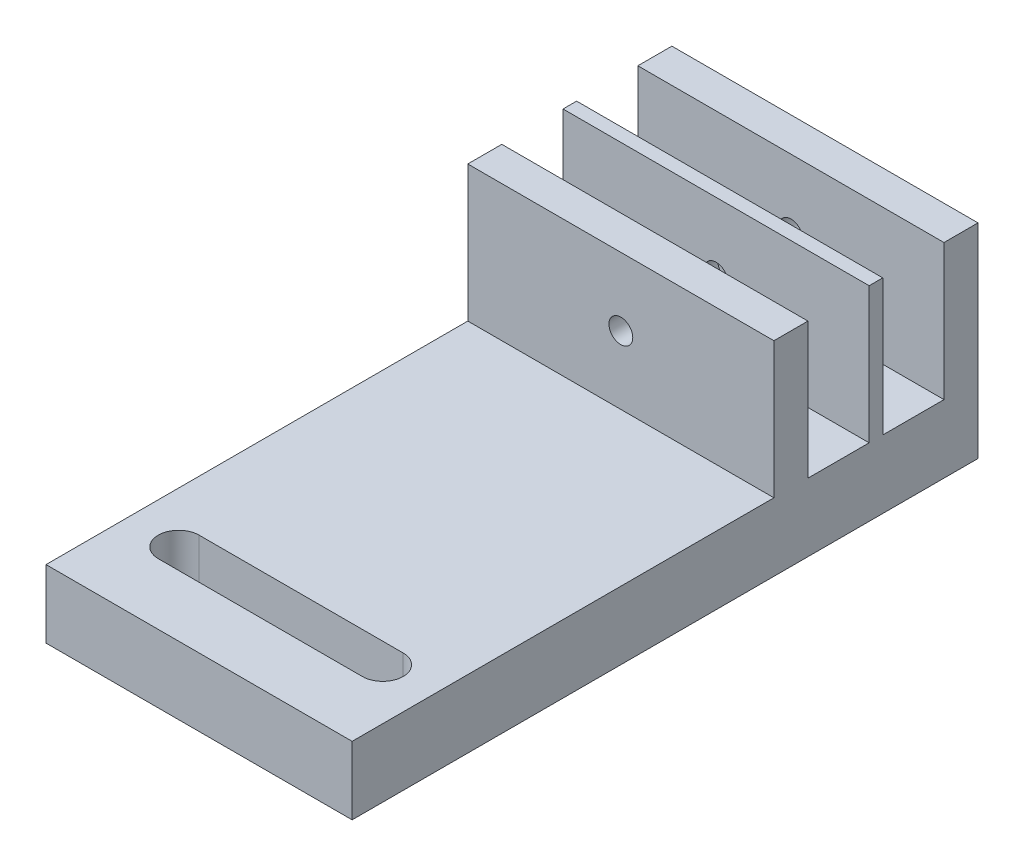
SolidWorks part; units mm, degrees
ref_plane "Front Plane" through (0, 0, 0) normal (0, 0, 1) x (1, 0, 0)
ref_plane "Top Plane" through (0, 0, 0) normal (0, 1, 0) x (1, 0, 0)
ref_plane "Right Plane" through (0, 0, 0) normal (1, 0, 0) x (0, 0, -1)
sketch "Sketch1" plane through (0, 0, 0) normal (0, 1, 0) x (1, 0, 0)
  line L0 (0, -55) -> (0, 55) construction
  line L1 (22.5, -28.5) -> (-22.5, -28.5)
  line L2 (22.5, -28.5) -> (22.5, 28.5)
  line L3 (22.5, 28.5) -> (-22.5, 28.5)
  line L4 (-22.5, -28.5) -> (-22.5, 28.5)
  line L5 (22.5, -28.5) -> (-22.5, 28.5) construction
  line L6 (22.5, 28.5) -> (-22.5, -28.5) construction
  line L7 (22.5, 18.5) -> (-22.5, 18.5) construction
  line L9 (-15, -13.5) -> (15, -13.5)
  line L10 (-15, -13.5) -> (-15, -19.5)
  line L11 (-15, -19.5) -> (15, -19.5)
  line L12 (15, -13.5) -> (15, -19.5)
  circle A0 centre (-15, -16.5) radius 3
  circle A1 centre (15, -16.5) radius 3
  point P0 (0, 0)
  dimension "D2" = 6
  dimension "D1" = 30
  dimension "D3" = 47
  dimension "D4" = 57
  dimension "D5" = 35
  dimension "D6" = 45
  dimension "D7" = 45
extrude "Boss-Extrude1" add sketch "Sketch1" along normal blind 10 contours L4 L1 L2 L3 L9 A1 L11 A0
sketch "Sketch4" plane through (0, 0, -28.5) normal (0, 0, -1) x (-1, 0, 0)
  line L0 (22.5, 0) -> (-31.8826, 0) construction
  line L2 (-22.5, 10) -> (22.5, 10)
  line L3 (-22.5, 10) -> (-22.5, 0)
  line L4 (-22.5, 0) -> (22.5, 0)
  line L5 (22.5, 10) -> (22.5, 0)
extrude "Boss-Extrude4" add sketch "Sketch4" along normal blind 35
sketch "Sketch5" plane through (22.5, 0, 0) normal (1, 0, 0) x (0, 0, -1)
  line L0 (-28.5, 10) -> (63.5, 10) construction
  line L5 (38.5, 10) -> (33.5, 10)
  line L6 (38.5, 10) -> (38.5, 30)
  line L7 (38.5, 30) -> (33.5, 30)
  line L8 (33.5, 10) -> (33.5, 30)
  line L9 (-13.5, 10) -> (-19.5, 10) construction
  line L10 (63.5, 10) -> (58.5, 10)
  line L11 (63.5, 10) -> (63.5, 30)
  line L12 (63.5, 30) -> (58.5, 30)
  line L13 (58.5, 10) -> (58.5, 30)
  line L14 (49.5, 10) -> (47.5, 10)
  line L15 (49.5, 10) -> (49.5, 30)
  line L16 (49.5, 30) -> (47.5, 30)
  line L17 (47.5, 10) -> (47.5, 30)
  line L18 (-13.5, 10) -> (-19.5, 10)
  line L19 (-16.5, 10) -> (-16.5, 0) construction
  line L23 (-19.5, 0) -> (-13.5, 0)
  line L24 (-13.5, 0) -> (-13.5, 10)
  line L25 (-13.5, 10) -> (-19.5, 10)
  line L26 (-19.5, 10) -> (-19.5, 0)
  line L27 (-19.5, 0) -> (-13.5, 0)
  line L28 (-13.5, 0) -> (-13.5, 10)
  line L29 (-13.5, 10) -> (-19.5, 10)
  line L30 (-19.5, 10) -> (-19.5, 0)
  line M7 (63.5, 10) -> (-28.5, 10)
  dimension "D1" = 9
  dimension "D2" = 9
  dimension "D4" = 55
  dimension "D5" = 20
  dimension "D6" = 11
  dimension "D3" = 0
extrude "Boss-Extrude5" add sketch "Sketch5" against normal up to surface (45 mm away) contours L8 L6 L7 M7 | L17 L15 L16 M7 | L13 L11 L12 M7 up to face at (-22.5, 5, -17.5)
sketch "Sketch6" plane through (0, 0, -33.5) normal (0, 0, 1) x (1, 0, 0)
  line L0 (0, -55) -> (0, 55) construction
  line L2 (22.5, 10) -> (-22.5, 10) construction
  circle A0 centre (0, 20) radius 1.75
  dimension "D1" = 3.5
  dimension "D2" = 10
extrude "Cut-Extrude1" cut sketch "Sketch6" against normal up to surface (30 mm away)
